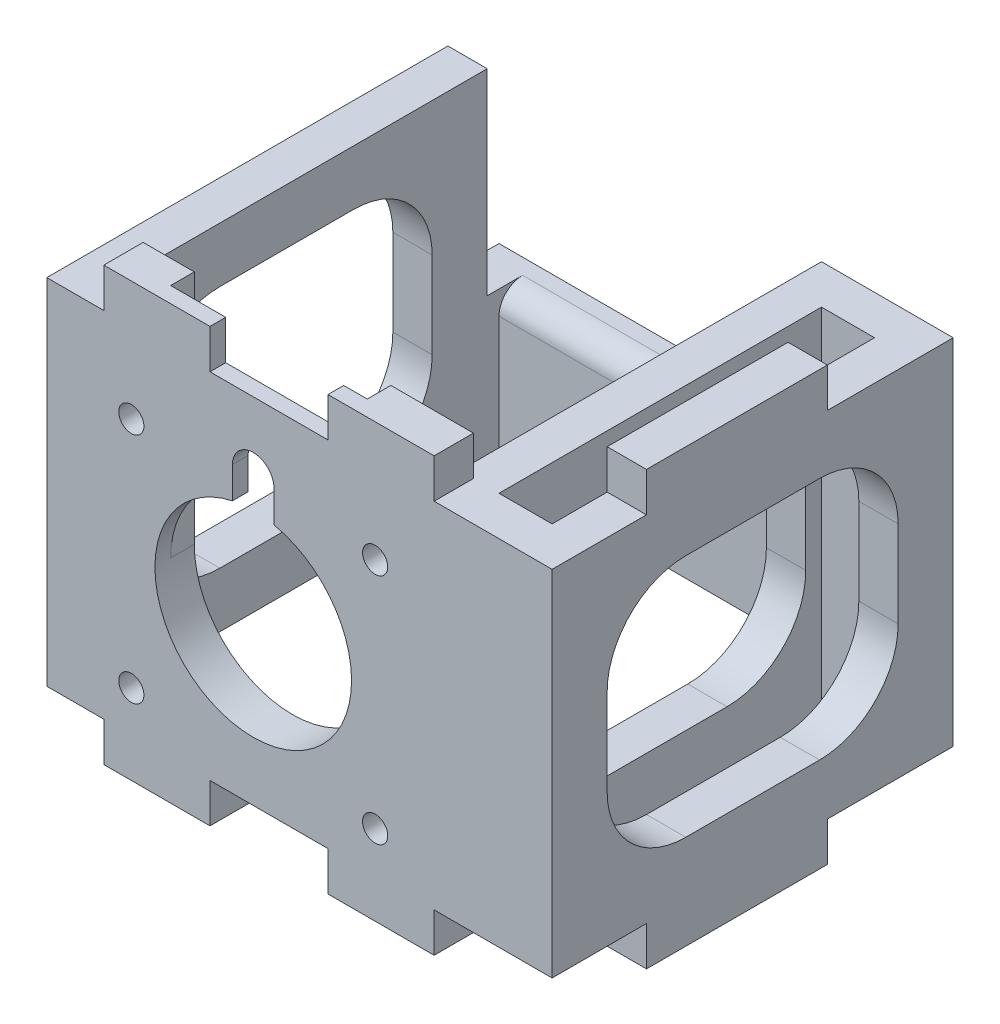
SolidWorks part; units mm, degrees
ref_plane "Plan de face" through (0, 0, 0) normal (0, 0, 1) x (1, 0, 0)
ref_plane "Plan de dessus" through (0, 0, 0) normal (0, 1, 0) x (1, 0, 0)
ref_plane "Plan de droite" through (0, 0, 0) normal (1, 0, 0) x (0, 0, -1)
sketch "Esquisse1" plane through (0, 0, 0) normal (0, 1, 0) x (1, 0, 0)
  line L1 (21.25, 23.75) -> (-21.25, 23.75)
  line L2 (21.25, 23.75) -> (21.25, -23.75)
  line L3 (21.25, -23.75) -> (-21.25, -23.75)
  line L4 (-21.25, 23.75) -> (-21.25, -23.75)
  line L5 (21.25, 23.75) -> (-21.25, -23.75) construction
  line L6 (21.25, -23.75) -> (-21.25, 23.75) construction
  point P0 (0, 0)
  dimension "D1" = 47.5
  dimension "D2" = 42.5
extrude "Extru.-Mince1" add sketch "Esquisse1" along normal blind 20 thin
sketch "Esquisse3" plane through (0, 0, 0) normal (0, -1, 0) x (1, 0, 0)
  line L0 (26.25, 28.75) -> (38, 28.75)
  line L1 (38, 28.75) -> (38, -22.25)
  line L3 (38, -22.25) -> (21.25, -22.25)
  line L4 (21.25, 23.75) -> (21.25, -23.75) construction
  line L5 (26.25, 28.75) -> (0, 28.75)
  line L6 (0, 28.75) -> (-26.25, 28.75)
  line L7 (-26.25, 28.75) -> (-62, 28.75)
  line L8 (-62, 28.75) -> (-62, -22.25)
  line L9 (-62, -22.25) -> (-21.25, -22.25)
  line L10 (-26.25, -28.75) -> (-26.25, 28.75) construction
  line L11 (33, 23.75) -> (33, -17.25)
  line L12 (33, -17.25) -> (26.25, -17.25)
  line L13 (26.25, 28.75) -> (26.25, -28.75) construction
  line L14 (26.25, -17.25) -> (26.25, 23.75)
  line L15 (26.25, 23.75) -> (33, 23.75)
  line L16 (-57, -17.25) -> (-26.25, -17.25)
  line L17 (-21.25, -23.75) -> (-21.25, 23.75) construction
  line L18 (-57, -17.25) -> (-57, 23.75)
  line L19 (-57, 23.75) -> (-26.25, 23.75)
  line L20 (-21.25, 23.75) -> (21.25, 23.75)
  line L21 (21.25, 23.75) -> (21.25, -22.25)
  line L22 (-21.25, 23.75) -> (-21.25, -22.25)
  line L23 (-26.25, 23.75) -> (-26.25, -17.25)
  line L24 (-26.25, 28.75) -> (26.25, 28.75) construction
  point P6 (26.25, 28.75)
  point P7 (-26.25, 28.75)
  dimension "D1" = 51
  dimension "D2" = 38
  dimension "D3" = 62
  dimension "D4" = 5
  dimension "D5" = 5
  dimension "D6" = 5
  dimension "D7" = 5
  dimension "D8" = 5
  dimension "D9" = 5
extrude "Boss.-Extru.1" add sketch "Esquisse3" against normal blind 45
sketch "Esquisse6" plane through (0, 45, 0) normal (0, 1, 0) x (1, 0, 0)
  line L0 (38, 6.25) -> (33, 6.25)
  line L1 (38, 22.25) -> (38, -28.75) construction
  line L2 (33, 17.25) -> (33, -23.75) construction
  line L3 (33, 6.25) -> (33, -16.75)
  line L4 (33, -16.75) -> (38, -16.75)
  line L5 (38, -16.75) -> (38, 6.25)
  line L6 (23, -28.75) -> (23, -23.75)
  line L7 (38, -28.75) -> (-62, -28.75) construction
  line L8 (33, -23.75) -> (26.25, -23.75) construction
  line L9 (23, -23.75) -> (9.5, -23.75)
  line L10 (-21.25, -23.75) -> (21.25, -23.75) construction
  line L11 (9.5, -23.75) -> (9.5, -28.75)
  line L12 (9.5, -28.75) -> (23, -28.75)
  line L13 (-5.5, -28.75) -> (-5.5, -23.75)
  line L14 (-5.5, -23.75) -> (-19, -23.75)
  line L15 (-19, -23.75) -> (-19, -28.75)
  line L16 (-19, -28.75) -> (-5.5, -28.75)
  line L17 (-34, -28.75) -> (-34, -23.75)
  line L18 (-34, -23.75) -> (-47.5, -23.75)
  line L19 (-47.5, -23.75) -> (-47.5, -28.75)
  line L20 (-47.5, -28.75) -> (-34, -28.75)
  line L23 (-47.5, 22.25) -> (-34, 22.25)
  line L24 (-47.5, 17.25) -> (-47.5, 22.25)
  line L25 (-34, 17.25) -> (-47.5, 17.25)
  line L26 (-34, 22.25) -> (-34, 17.25)
  line L28 (-62, -16.75) -> (-62, 6.25)
  line L29 (-57, -16.75) -> (-62, -16.75)
  line L30 (-57, 6.25) -> (-57, -16.75)
  line L31 (-62, 6.25) -> (-57, 6.25)
  point P6 (38, -5.25)
  point P15 (38, -5.25)
  dimension "D1" = 23
  dimension "D2" = 13.5
  dimension "D3" = 15
  dimension "D5" = 23.5
  dimension "D6" = 12
  dimension "D4" = 3
extrude "Boss.-Extru.3" add sketch "Esquisse6" along normal blind 5
sketch "Esquisse2" plane through (0, 0, 28.75) normal (0, 0, 1) x (1, 0, 0)
  line L0 (-62, 0) -> (38, 0) construction
  line L1 (0, -0.0585) -> (0, 20) construction
  line L2 (-15.5, 5.2) -> (15.5, 5.2) construction
  line L3 (38, 45) -> (38, 0) construction
  line L4 (0, 36.2159) -> (0, 28.8659) construction
  line L5 (2.65, 36.2159) -> (2.65, 32.2159)
  line L6 (-62, 0) -> (38, 0) construction
  line L7 (0, 20) -> (33.7261, 20) construction
  line L8 (-15.5, 34.8) -> (15.5, 34.8) construction
  line L9 (-2.65, 36.2159) -> (-2.65, 32.2159)
  arc A0 (-2.65, 32.2159) -> (2.65, 32.2159) centre (0, 20) ccw
  circle A1 centre (-15.5, 5.2) radius 1.6
  circle A2 centre (15.5, 5.2) radius 1.6
  circle A3 centre (15.5, 34.8) radius 1.6
  circle A4 centre (-15.5, 34.8) radius 1.6
  arc A5 (2.65, 36.2159) -> (-2.65, 36.2159) centre (0, 36.2159) ccw
  point P6 (0, -0.0585)
  point P10 (0, 5.2)
  point P20 (0, 34.8)
  point P21 (0, 40.0585)
  point P24 (0, 32.5)
  dimension "D2" = 25
  dimension "D3" = 3.2
  dimension "D4" = 3.2
  dimension "D8" = 2.65
  dimension "D1" = 20
  dimension "D5" = 5.2
  dimension "D6" = 31
  dimension "D7" = 38
  dimension "D9" = 7.35
  dimension "D10" = 5.3
  dimension "D11" = 4
extrude "Enlèv. mat.-Extru.1" cut sketch "Esquisse2" against normal up to next
sketch "Esquisse4" plane through (0, 0, 23.75) normal (0, 0, -1) x (-1, 0, 0)
  line L0 (-12.5, 20) -> (-12.5, 50)
  line L2 (-23, 50) -> (-9.5, 50) construction
  line L3 (12.5, 50) -> (12.5, 20)
  line L4 (-12.5, 50) -> (12.5, 50)
  circle A0 centre (0, 20) radius 12.5 construction
  arc A1 (-12.5, 20) -> (12.5, 20) centre (0, 20) cw
  dimension "D1" = 25
extrude "Enlèv. mat.-Extru.2" cut sketch "Esquisse4" against normal blind 3
ref_plane "Plan1" through (0, 22.5, 0) normal (0, -1, 0) x (-1, 0, 0)
mirror "Symétrie1" about plane through (0, 22.5, 0) normal (0, -1, 0) of "Boss.-Extru.3"
ref_plane "Plan2" through (0, 0, 0) normal (1, 0, 0) x (0, 0, -1)
fillet "Congé1" radius 3 1 edges at (0, 20, -23.75)
sketch "Esquisse7" plane through (38, 0, 0) normal (1, 0, 0) x (0, 0, -1)
  line L0 (-16.75, 0) -> (-28.75, 0) construction
  line L1 (-11.75, 38) -> (5.25, 38)
  line L2 (-21.75, 28) -> (-21.75, 17)
  line L3 (-11.75, 7) -> (5.25, 7)
  line L4 (15.25, 28) -> (15.25, 17)
  line L5 (-21.75, 38) -> (15.25, 7) construction
  line L6 (-21.75, 7) -> (15.25, 38) construction
  line L7 (-16.75, 45) -> (-28.75, 45) construction
  line L8 (22.25, 45) -> (22.25, 0) construction
  line L9 (-28.75, 45) -> (-28.75, 0) construction
  arc A0 (5.25, 7) -> (15.25, 17) centre (5.25, 17) ccw
  arc A1 (-21.75, 17) -> (-11.75, 7) centre (-11.75, 17) ccw
  arc A2 (5.25, 38) -> (15.25, 28) centre (5.25, 28) cw
  arc A3 (-11.75, 38) -> (-21.75, 28) centre (-11.75, 28) ccw
  point P0 (-3.25, 22.5)
  dimension "D5" = 10
  dimension "D1" = 7
  dimension "D2" = 7
  dimension "D3" = 7
  dimension "D4" = 7
extrude "Enlèv. mat.-Extru.3" cut sketch "Esquisse7" against normal through all
sketch "Esquisse8" plane through (0, 0, -22.25) normal (0, 0, -1) x (-1, 0, 0)
  line L0 (41.625, 30) -> (41.625, 15) construction
  line L1 (48.625, 30) -> (48.625, 15)
  line L2 (34.625, 30) -> (34.625, 15)
  line L3 (62, 45) -> (62, 0) construction
  line L5 (62, 22.5) -> (21.25, 22.5) construction
  line L6 (21.25, 45) -> (21.25, 20) construction
  arc A0 (48.625, 30) -> (34.625, 30) centre (41.625, 30) ccw
  arc A1 (34.625, 15) -> (48.625, 15) centre (41.625, 15) ccw
  point P2 (41.625, 22.5)
  dimension "D2" = 7
  dimension "D1" = 15
extrude "Enlèv. mat.-Extru.4" cut sketch "Esquisse8" against normal through all
sketch "Esquisse10" plane through (0, 45, 0) normal (0, 1, 0) x (1, 0, 0)
  line L0 (-26.25, -28.75) -> (-26.25, 22.25)
  line L1 (-19, -28.75) -> (-34, -28.75) construction
  line L2 (-34, 22.25) -> (-21.25, 22.25) construction
  line L3 (-26.25, 22.25) -> (-62, 22.25)
  line L4 (-62, 22.25) -> (-62, -28.75)
  line L5 (-62, -28.75) -> (-26.25, -28.75)
  line L6 (-26.25, 17.25) -> (-26.25, -23.75) construction
  point P6 (-26.25, -3.25)
  point P17 (-26.25, -3.25)
extrude "Enlèv. mat.-Extru.5" cut sketch "Esquisse10" against normal through all both and the other way through all
